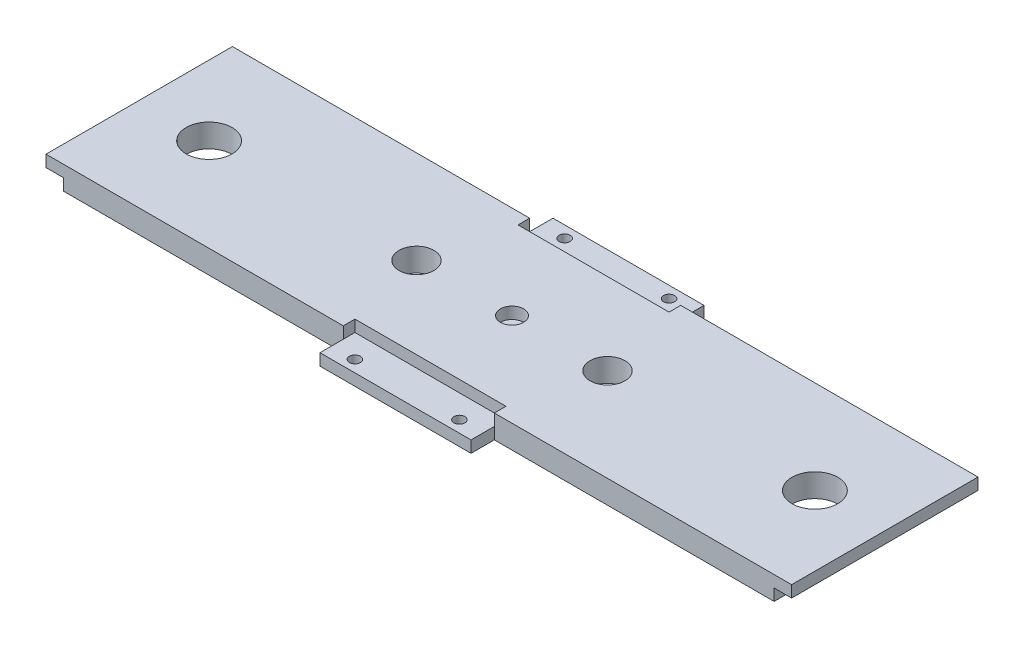
SolidWorks part; units mm, degrees
ref_plane "Front Plane" through (0, 0, 0) normal (0, 0, 1) x (1, 0, 0)
ref_plane "Top Plane" through (0, 0, 0) normal (0, 1, 0) x (1, 0, 0)
ref_plane "Right Plane" through (0, 0, 0) normal (1, 0, 0) x (0, 0, -1)
sketch "Sketch1" plane through (0, 0, 0) normal (0, 1, 0) x (1, 0, 0)
  line L0 (-101.6, 0) -> (-82.55, 0) construction
  line L1 (-101.6, -25.4) -> (101.6, -25.4)
  line L2 (-101.6, -25.4) -> (-101.6, 25.4)
  line L3 (-101.6, 25.4) -> (101.6, 25.4)
  line L4 (101.6, -25.4) -> (101.6, 25.4)
  line L5 (-101.6, -25.4) -> (101.6, 25.4) construction
  line L6 (-101.6, 25.4) -> (101.6, -25.4) construction
  line L7 (-15.5, 15.5) -> (15.5, 15.5) construction
  line L8 (-15.5, 15.5) -> (-15.5, -15.5) construction
  line L11 (-15.5, 15.5) -> (15.5, -15.5) construction
  line L12 (-15.5, -15.5) -> (15.5, 15.5) construction
  line L13 (0, 25.4) -> (0, -25.4) construction
  line L14 (101.6, 0) -> (82.55, 0) construction
  line L15 (-15.5, -15.5) -> (15.5, -15.5) construction
  line L16 (15.5, -15.5) -> (15.5, 15.5) construction
  circle A4 centre (-82.55, 0) radius 6.25
  circle A5 centre (82.55, 0) radius 6.25
  circle A6 centre (0, 0) radius 3.175
  point P0 (0, 0)
  point P6 (0, 0)
  point P21 (0, 0)
  dimension "D7" = 12.5
  dimension "D8" = 6.35
  dimension "D1" = 203.2
  dimension "D2" = 50.8
  dimension "D3" = 31
  dimension "D6" = 19.05
  dimension "D9" = 82.55
extrude "Boss-Extrude1" add sketch "Sketch1" along normal blind 6.35
sketch "Sketch2" plane through (0, 6.35, 0) normal (0, 1, 0) x (1, 0, 0)
  line L0 (-15.5, -15.5) -> (-20.58, -15.5) construction
  line L3 (15.5, -15.5) -> (20.58, -15.5) construction
  line L4 (20.58, -25.4) -> (20.58, -22.225)
  line L5 (-101.6, -25.4) -> (101.6, -25.4) construction
  line L6 (20.58, -22.225) -> (-20.58, -22.225)
  line L7 (-20.58, -22.225) -> (-20.58, -25.4)
  line L8 (-20.58, -25.4) -> (20.58, -25.4)
  line L9 (-82.55, 0) -> (82.55, 0) construction
  line L10 (-20.58, 25.4) -> (20.58, 25.4)
  line L11 (-20.58, 22.225) -> (-20.58, 25.4)
  line L12 (20.58, 22.225) -> (-20.58, 22.225)
  line L13 (20.58, 25.4) -> (20.58, 22.225)
  dimension "D1" = 5.08
  dimension "D2" = 3.175
extrude "Cut-Extrude1" cut sketch "Sketch2" against normal blind 3.175
sketch "Sketch3" plane through (0, 0, 0) normal (0, -1, 0) x (1, 0, 0)
  line L0 (-101.6, 25.4) -> (-96.8375, 25.4)
  line L3 (-101.6, 25.4) -> (101.6, 25.4) construction
  line L6 (101.6, -25.4) -> (-101.6, -25.4) construction
  line L8 (0, 25.4) -> (0, -25.4) construction
  line L13 (-96.8375, 25.4) -> (-96.8375, -25.4)
  line L14 (-96.8375, -25.4) -> (-101.6, -25.4)
  line L16 (-101.6, -25.4) -> (-101.6, 25.4) construction
  line L17 (-101.6, -25.4) -> (-101.6, 25.4)
  line L18 (101.6, -25.4) -> (101.6, 25.4)
  line L19 (96.8375, -25.4) -> (101.6, -25.4)
  line L20 (96.8375, 25.4) -> (96.8375, -25.4)
  line L21 (101.6, 25.4) -> (96.8375, 25.4)
  dimension "D1" = 4.7625
extrude "Cut-Extrude2" cut sketch "Sketch3" against normal blind 3.175
sketch "Sketch4" plane through (0, 6.35, 0) normal (0, 1, 0) x (1, 0, 0)
  line L0 (0, 25.4) -> (0, -25.4) construction
  line L1 (20.58, 25.4) -> (-20.58, 25.4) construction
  line L2 (-20.58, -25.4) -> (20.58, -25.4) construction
  circle A0 centre (0, 0) radius 7.62 construction
  circle A1 centre (-26.035, 0) radius 18.415 construction
  circle A3 centre (-26.035, 0) radius 4.7625
  circle A4 centre (26.035, 0) radius 4.7625
  circle A6 centre (-82.55, 0) radius 38.1 construction
  dimension "D1" = 15.24
  dimension "D2" = 36.83
  dimension "D3" = 76.2
  dimension "D4" = 9.525
extrude "Cut-Extrude3" cut sketch "Sketch4" against normal through all
sketch "Sketch5" plane through (0, 0, -25.4) normal (0, 0, -1) x (-1, 0, 0)
  line L0 (-20.58, 3.175) -> (20.58, 3.175) construction
  line L1 (-20.58, 3.175) -> (20.58, 3.175)
  line L2 (-20.58, 3.175) -> (-20.58, 0)
  line L3 (-96.8375, 0) -> (96.8375, 0) construction
  line L4 (-20.58, 0) -> (20.58, 0)
  line L5 (20.58, 0) -> (20.58, 3.175)
extrude "Boss-Extrude2" add sketch "Sketch5" along normal blind 6.35 and the other way blind 57.15
sketch "Sketch6" plane through (0, 3.175, 0) normal (0, 1, 0) x (1, 0, 0)
  line L1 (-20.58, 25.4) -> (20.58, 25.4) construction
  line L4 (-20.58, 25.4) -> (-20.58, 31.75) construction
  line L5 (-20.58, 25.4) -> (-20.58, 31.75) construction
  line L6 (-20.58, 28.575) -> (-14.23, 28.575) construction
  line L7 (0, 0) -> (0, 31.75) construction
  line L8 (-20.58, 31.75) -> (20.58, 31.75) construction
  line L9 (-26.0938, 0) -> (26.0938, 0) construction
  circle A0 centre (-14.23, 28.575) radius 1.5
  circle A1 centre (14.23, 28.575) radius 1.5
  circle A2 centre (14.23, -28.575) radius 1.5
  circle A3 centre (-14.23, -28.575) radius 1.5
  point P17 (0, 0)
  dimension "D2" = 3
  dimension "D1" = 6.35
extrude "Cut-Extrude4" cut sketch "Sketch6" against normal blind 6.35
